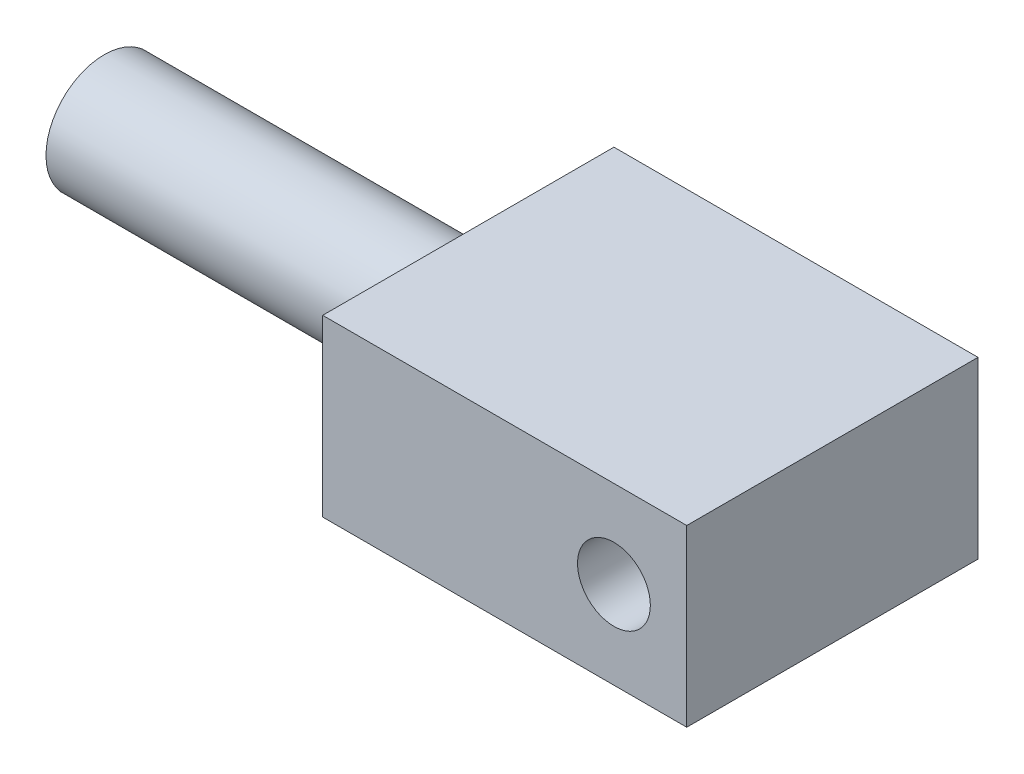
SolidWorks part; units mm, degrees
ref_plane "Спереди" through (0, 0, 0) normal (0, 0, 1) x (1, 0, 0)
ref_plane "Сверху" through (0, 0, 0) normal (0, 1, 0) x (1, 0, 0)
ref_plane "Справа" through (0, 0, 0) normal (1, 0, 0) x (0, 0, -1)
sketch "Эскиз1" plane through (0, 0, 0) normal (1, 0, 0) x (0, 0, -1)
  line L0 (-20, -40.6306) -> (-68.5325, -40.6306) construction
  line L1 (-20, -34.6306) -> (0, -34.6306)
  line L2 (-20, -34.6306) -> (-20, -46.6306)
  line L3 (-20, -46.6306) -> (0, -46.6306)
  line L4 (0, -34.6306) -> (0, -46.6306)
  point P0 (0, 0)
  dimension "D1" = 6
  dimension "D2" = 6
extrude "Вытянуть1" add sketch "Эскиз1" along normal blind 25
sketch "Эскиз5" plane through (0, 0, 20) normal (0, 0, 1) x (1, 0, 0)
  line L0 (0, -34.6306) -> (0, -46.6306) construction
  circle A0 centre (20, -40.6306) radius 2.5
  dimension "D1" = 20
extrude "Вырез-Вытянуть2" cut sketch "Эскиз5" against normal through all
sketch "Sketch1" plane through (0, 0, 0) normal (-1, 0, 0) x (0, 0, 1)
  circle A0 centre (10, -40.6306) radius 4
extrude "Boss-Extrude1" add sketch "Sketch1" along normal blind 25
